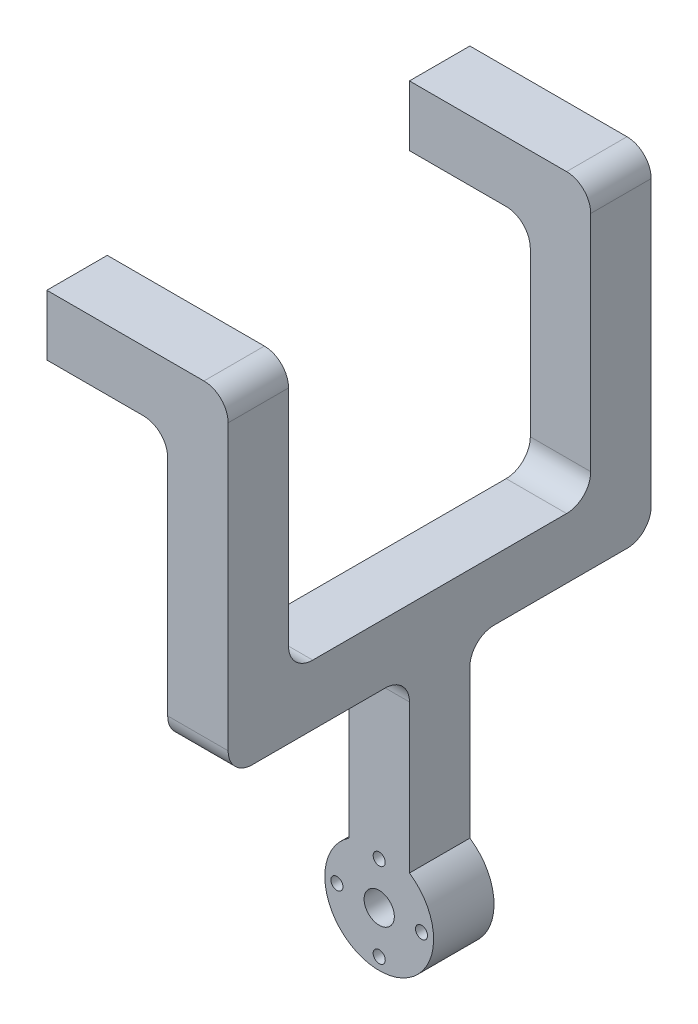
SolidWorks part; units mm, degrees
ref_plane "Plan de face" through (0, 0, 0) normal (0, 0, 1) x (1, 0, 0)
ref_plane "Plan de dessus" through (0, 0, 0) normal (0, 1, 0) x (1, 0, 0)
ref_plane "Plan de droite" through (0, 0, 0) normal (1, 0, 0) x (0, 0, -1)
sketch "Esquisse1" plane through (0, 0, 0) normal (0, 0, 1) x (1, 0, 0)
  line L0 (9, 0) -> (9, 9) construction
  line L1 (0, 0) -> (18, 0) construction
  line L2 (0, 0) -> (0, 55) construction
  line L3 (0, 55) -> (18, 55) construction
  line L4 (18, 0) -> (18, 55) construction
  line L5 (9, 9) -> (0, 9) construction
  line L6 (9, 9) -> (9, 16) construction
  line L7 (4, 55) -> (14, 55)
  line L8 (4, 55) -> (4, 16.4833)
  line L10 (14, 55) -> (14, 16.4833)
  arc A0 (4, 16.4833) -> (14, 16.4833) centre (9, 9) ccw
  circle A1 centre (9, 9) radius 2.5
  circle A2 centre (9, 16) radius 1
  circle A3 centre (16, 9) radius 1
  circle A4 centre (9, 2) radius 1
  circle A5 centre (2, 9) radius 1
  point P24 (9, 9)
  dimension "D4" = 18
  dimension "D7" = 5
  dimension "D9" = 2
  dimension "D1" = 18
  dimension "D2" = 55
  dimension "D3" = 9
  dimension "D5" = 10
  dimension "D6" = 4
  dimension "D8" = 7
  dimension "D10" = 4
extrude "Boss.-Extru.1" add sketch "Esquisse1" along normal blind 10
sketch "Esquisse4" plane through (14, 0, 0) normal (1, 0, 0) x (0, 0, -1)
  line L0 (-30, 55) -> (20, 55)
  line L1 (20, 100) -> (30, 100)
  line L2 (30, 100) -> (30, 45)
  line L3 (30, 45) -> (-40, 45)
  line L4 (-40, 45) -> (-40, 100)
  line L5 (-40, 100) -> (-30, 100)
  line L6 (-30, 100) -> (-30, 55)
  line L8 (20, 55) -> (20, 100)
  line L9 (-5, 55) -> (-5, 16.4833) construction
  line L10 (-10, 55) -> (0, 55) construction
  line L11 (-10, 16.4833) -> (0, 16.4833) construction
  point P5 (-5, 55)
  point P15 (-5, 45)
  dimension "D1" = 70
  dimension "D2" = 10
  dimension "D3" = 10
  dimension "D4" = 100
  dimension "D5" = 100
extrude "Boss.-Extru.2" add sketch "Esquisse4" against normal blind 10
sketch "Esquisse5" plane through (4, 0, 0) normal (-1, 0, 0) x (0, 0, 1)
  line L0 (-20, 100) -> (-20, 55) construction
  line L1 (-30, 100) -> (-20, 100)
  line L2 (-30, 100) -> (-30, 90)
  line L3 (-30, 90) -> (-20, 90)
  line L4 (-20, 100) -> (-20, 90)
  line L5 (40, 100) -> (40, 45) construction
  line L6 (30, 100) -> (40, 100)
  line L7 (30, 100) -> (30, 90)
  line L8 (30, 90) -> (40, 90)
  line L9 (40, 100) -> (40, 90)
  dimension "D1" = 10
extrude "Boss.-Extru.3" add sketch "Esquisse5" along normal blind 20
fillet "Congé1" radius 4 10 edges at (9, 55, -20) (9, 55, 30) (4, 90, -25) (4, 90, 35) (9, 45, -30) (9, 45, 40) (14, 100, -25) (14, 100, 35) (9, 45, 0) (9, 45, 10)
equation "\"D3@Esquisse1\"=\"D1@Esquisse1\"/2"
equation "\"D4@Esquisse1\"=\"D1@Esquisse1\""
equation "\"D6@Esquisse1\"=(\"D1@Esquisse1\"-\"D5@Esquisse1\")/2"
